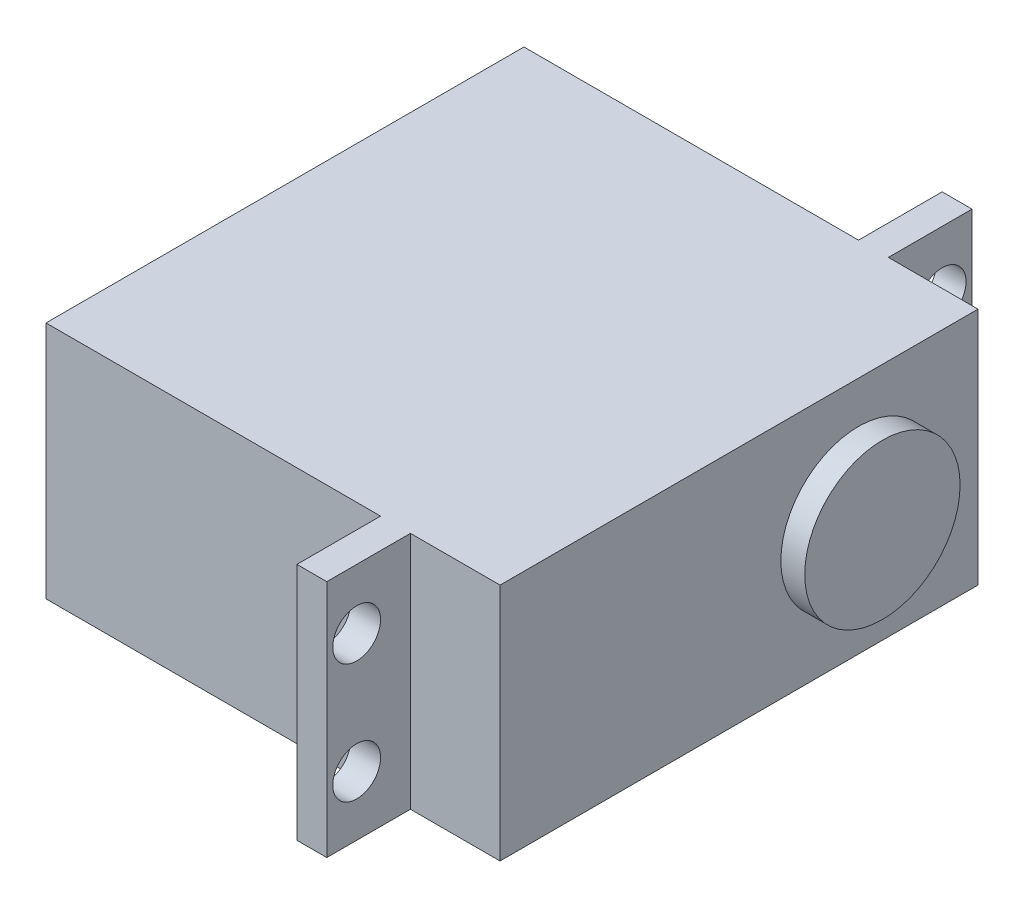
SolidWorks part; units mm, degrees
ref_plane "Front Plane" through (0, 0, 0) normal (0, 0, 1) x (1, 0, 0)
ref_plane "Top Plane" through (0, 0, 0) normal (0, 1, 0) x (1, 0, 0)
ref_plane "Right Plane" through (0, 0, 0) normal (1, 0, 0) x (0, 0, -1)
sketch "Sketch1" plane through (0, 0, 0) normal (0, 1, 0) x (1, 0, 0)
  line L0 (11.5, 20) -> (19, 20)
  line L1 (-19, 20) -> (9, 20)
  line L2 (-19, 20) -> (-19, -20)
  line L3 (-19, -20) -> (9, -20)
  line L4 (19, 20) -> (19, -20)
  line L5 (-19, 20) -> (19, -20) construction
  line L6 (-19, -20) -> (19, 20) construction
  line L7 (9, 27) -> (11.5, 27)
  line L8 (9, 27) -> (9, 20)
  line L9 (11.5, -20) -> (19, -20)
  line L10 (11.5, 27) -> (11.5, 20)
  line L11 (9, 27) -> (11.5, 20) construction
  line L12 (9, 20) -> (11.5, 27) construction
  line L13 (9, -27) -> (11.5, -27)
  line L14 (9, -27) -> (9, -20)
  line L16 (11.5, -27) -> (11.5, -20)
  line L17 (9, -27) -> (11.5, -20) construction
  line L18 (9, -20) -> (11.5, -27) construction
  point P0 (0, 0)
  point P6 (10.25, 23.5)
  point P11 (10.25, -23.5)
  dimension "D1" = 38
  dimension "D2" = 40
  dimension "D3" = 7
  dimension "D4" = 7
  dimension "D5" = 2.5
  dimension "D6" = 2.5
  dimension "D7" = 10
  dimension "D8" = 10
extrude "Boss-Extrude1" add sketch "Sketch1" along normal blind 20
sketch "Sketch2" plane through (11.5, 0, 0) normal (1, 0, 0) x (0, 0, -1)
  line L0 (-27, 20) -> (-27, 0) construction
  line L1 (27, 20) -> (27, 0) construction
  line L2 (24.5, 15) -> (24.5, 5) construction
  line L3 (20, 20) -> (27, 20) construction
  circle A0 centre (-24.5, 15) radius 2
  circle A1 centre (-24.5, 5) radius 2
  circle A2 centre (24.5, 5) radius 2
  circle A3 centre (24.5, 15) radius 2
  point P12 (24.5, 10)
  point P13 (23.5, 20)
  dimension "D1" = 4
  dimension "D2" = 2.5
  dimension "D3" = 2.5
  dimension "D4" = 10
  dimension "D5" = 10
extrude "Cut-Extrude1" cut sketch "Sketch2" against normal up to surface (2.5 mm away) up to face at (9, 10, 23.5)
sketch "Sketch3" plane through (19, 0, 0) normal (1, 0, 0) x (0, 0, -1)
  line L0 (20, 20) -> (20, 0) construction
  line L1 (-20, 20) -> (20, 20) construction
  circle A0 centre (10, 10) radius 6.5
  dimension "D1" = 13
  dimension "D2" = 10
  dimension "D3" = 10
extrude "Boss-Extrude2" add sketch "Sketch3" along normal blind 2
